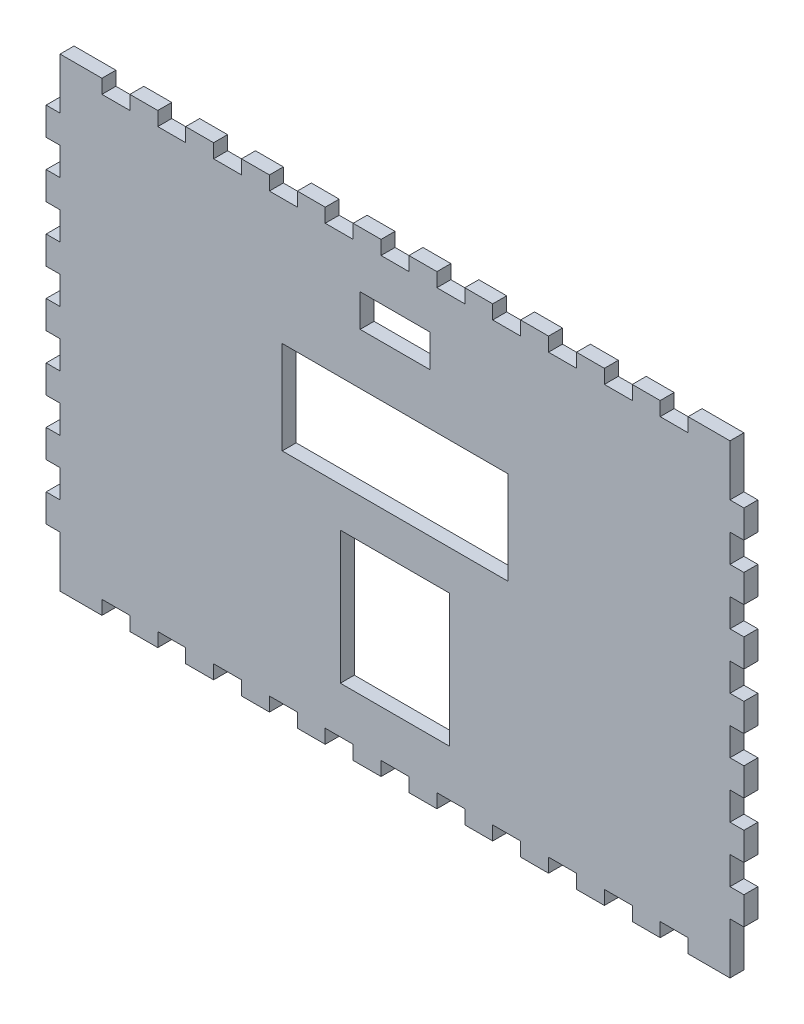
SolidWorks part; units mm, degrees
ref_plane "Front Plane" through (0, 0, 0) normal (0, 0, 1) x (1, 0, 0)
ref_plane "Top Plane" through (0, 0, 0) normal (0, 1, 0) x (1, 0, 0)
ref_plane "Right Plane" through (0, 0, 0) normal (1, 0, 0) x (0, 0, -1)
sketch "Model" plane through (0, 0, 0) normal (0, 0, 1) x (1, 0, 0)
  line L0 (209, 406) -> (209, 384)
  line L1 (209, 384) -> (203, 384)
  line L2 (203, 384) -> (203, 372)
  line L3 (203, 372) -> (209, 372)
  line L4 (209, 372) -> (209, 360)
  line L5 (209, 360) -> (203, 360)
  line L6 (203, 360) -> (203, 348)
  line L7 (203, 348) -> (209, 348)
  line L8 (209, 348) -> (209, 336)
  line L9 (209, 336) -> (203, 336)
  line L10 (203, 336) -> (203, 324)
  line L11 (203, 324) -> (209, 324)
  line L12 (209, 324) -> (209, 312)
  line L13 (209, 312) -> (203, 312)
  line L14 (203, 312) -> (203, 300)
  line L15 (203, 300) -> (209, 300)
  line L16 (209, 300) -> (209, 288)
  line L17 (209, 288) -> (203, 288)
  line L18 (203, 288) -> (203, 276)
  line L19 (203, 276) -> (209, 276)
  line L20 (209, 276) -> (209, 264)
  line L21 (209, 264) -> (203, 264)
  line L22 (203, 264) -> (203, 252)
  line L23 (203, 252) -> (209, 252)
  line L24 (209, 252) -> (209, 240)
  line L25 (209, 240) -> (203, 240)
  line L26 (203, 240) -> (203, 228)
  line L27 (203, 228) -> (209, 228)
  line L28 (209, 228) -> (209, 216)
  line L29 (209, 216) -> (209, 206)
  line L30 (209, 206) -> (227, 206)
  line L31 (227, 206) -> (227, 212)
  line L32 (227, 212) -> (239, 212)
  line L33 (239, 212) -> (239, 206)
  line L34 (239, 206) -> (251, 206)
  line L35 (251, 206) -> (251, 212)
  line L36 (251, 212) -> (263, 212)
  line L37 (263, 212) -> (263, 206)
  line L38 (263, 206) -> (275, 206)
  line L39 (275, 206) -> (275, 212)
  line L40 (275, 212) -> (287, 212)
  line L41 (287, 212) -> (287, 206)
  line L42 (287, 206) -> (299, 206)
  line L43 (299, 206) -> (299, 212)
  line L44 (299, 212) -> (311, 212)
  line L45 (311, 212) -> (311, 206)
  line L46 (311, 206) -> (323, 206)
  line L47 (323, 206) -> (323, 212)
  line L48 (323, 212) -> (335, 212)
  line L49 (335, 212) -> (335, 206)
  line L50 (335, 206) -> (347, 206)
  line L51 (347, 206) -> (347, 212)
  line L52 (347, 212) -> (359, 212)
  line L53 (359, 212) -> (359, 206)
  line L54 (359, 206) -> (371, 206)
  line L55 (371, 206) -> (371, 212)
  line L56 (371, 212) -> (383, 212)
  line L57 (383, 212) -> (383, 206)
  line L58 (383, 206) -> (395, 206)
  line L59 (395, 206) -> (395, 212)
  line L60 (395, 212) -> (407, 212)
  line L61 (407, 212) -> (407, 206)
  line L62 (407, 206) -> (419, 206)
  line L63 (419, 206) -> (419, 212)
  line L64 (419, 212) -> (431, 212)
  line L65 (431, 212) -> (431, 206)
  line L66 (431, 206) -> (443, 206)
  line L67 (443, 206) -> (443, 212)
  line L68 (443, 212) -> (455, 212)
  line L69 (455, 212) -> (455, 206)
  line L70 (455, 206) -> (467, 206)
  line L71 (467, 206) -> (467, 212)
  line L72 (467, 212) -> (479, 212)
  line L73 (479, 212) -> (479, 206)
  line L74 (479, 206) -> (491, 206)
  line L75 (491, 206) -> (497, 206)
  line L76 (497, 206) -> (497, 228)
  line L77 (497, 228) -> (503, 228)
  line L78 (503, 228) -> (503, 240)
  line L79 (503, 240) -> (497, 240)
  line L80 (497, 240) -> (497, 252)
  line L81 (497, 252) -> (503, 252)
  line L82 (503, 252) -> (503, 264)
  line L83 (503, 264) -> (497, 264)
  line L84 (497, 264) -> (497, 276)
  line L85 (497, 276) -> (503, 276)
  line L86 (503, 276) -> (503, 288)
  line L87 (503, 288) -> (497, 288)
  line L88 (497, 288) -> (497, 300)
  line L89 (497, 300) -> (503, 300)
  line L90 (503, 300) -> (503, 312)
  line L91 (503, 312) -> (497, 312)
  line L92 (497, 312) -> (497, 324)
  line L93 (497, 324) -> (503, 324)
  line L94 (503, 324) -> (503, 336)
  line L95 (503, 336) -> (497, 336)
  line L96 (497, 336) -> (497, 348)
  line L97 (497, 348) -> (503, 348)
  line L98 (503, 348) -> (503, 360)
  line L99 (503, 360) -> (497, 360)
  line L100 (497, 360) -> (497, 372)
  line L101 (497, 372) -> (503, 372)
  line L102 (503, 372) -> (503, 384)
  line L103 (503, 384) -> (497, 384)
  line L104 (497, 384) -> (497, 396)
  line L105 (497, 396) -> (497, 406)
  line L106 (497, 406) -> (479, 406)
  line L107 (479, 406) -> (479, 400)
  line L108 (479, 400) -> (467, 400)
  line L109 (467, 400) -> (467, 406)
  line L110 (467, 406) -> (455, 406)
  line L111 (455, 406) -> (455, 400)
  line L112 (455, 400) -> (443, 400)
  line L113 (443, 400) -> (443, 406)
  line L114 (443, 406) -> (431, 406)
  line L115 (431, 406) -> (431, 400)
  line L116 (431, 400) -> (419, 400)
  line L117 (419, 400) -> (419, 406)
  line L118 (419, 406) -> (407, 406)
  line L119 (407, 406) -> (407, 400)
  line L120 (407, 400) -> (395, 400)
  line L121 (395, 400) -> (395, 406)
  line L122 (395, 406) -> (383, 406)
  line L123 (383, 406) -> (383, 400)
  line L124 (383, 400) -> (371, 400)
  line L125 (371, 400) -> (371, 406)
  line L126 (371, 406) -> (359, 406)
  line L127 (359, 406) -> (359, 400)
  line L128 (359, 400) -> (347, 400)
  line L129 (347, 400) -> (347, 406)
  line L130 (347, 406) -> (335, 406)
  line L131 (335, 406) -> (335, 400)
  line L132 (335, 400) -> (323, 400)
  line L133 (323, 400) -> (323, 406)
  line L134 (323, 406) -> (311, 406)
  line L135 (311, 406) -> (311, 400)
  line L136 (311, 400) -> (299, 400)
  line L137 (299, 400) -> (299, 406)
  line L138 (299, 406) -> (287, 406)
  line L139 (287, 406) -> (287, 400)
  line L140 (287, 400) -> (275, 400)
  line L141 (275, 400) -> (275, 406)
  line L142 (275, 406) -> (263, 406)
  line L143 (263, 406) -> (263, 400)
  line L144 (263, 400) -> (251, 400)
  line L145 (251, 400) -> (251, 406)
  line L146 (251, 406) -> (239, 406)
  line L147 (239, 406) -> (239, 400)
  line L148 (239, 400) -> (227, 400)
  line L149 (227, 400) -> (227, 406)
  line L150 (227, 406) -> (215, 406)
  line L151 (215, 406) -> (209, 406)
extrude "Boss-Extrude1" add sketch "Model" along normal blind 6
sketch "Sketch2" plane through (0, 0, 6) normal (0, 0, 1) x (1, 0, 0)
  line L0 (368, 375) -> (503, 375)
  line L1 (338, 382) -> (368, 382)
  line L2 (338, 382) -> (338, 368)
  line L3 (338, 368) -> (368, 368)
  line L4 (368, 382) -> (368, 368)
  line L6 (338, 375) -> (203, 375)
  line L8 (401.5, 326) -> (497, 326)
  line L9 (304.5, 346) -> (401.5, 346)
  line L10 (304.5, 346) -> (304.5, 306)
  line L11 (304.5, 306) -> (401.5, 306)
  line L12 (401.5, 346) -> (401.5, 306)
  line L13 (497, 288) -> (497, 300) construction
  line L14 (304.5, 326) -> (209, 326)
  line L15 (209, 300) -> (209, 288) construction
  line L16 (503, 348) -> (503, 360) construction
  line L17 (203, 360) -> (203, 348) construction
  line L18 (371, 212) -> (383, 212) construction
  line L19 (329.5, 289) -> (376.5, 289)
  line L20 (329.5, 289) -> (329.5, 232)
  line L21 (329.5, 232) -> (376.5, 232)
  line L22 (376.5, 289) -> (376.5, 232)
  line L23 (376.5, 260.5) -> (497, 260.5)
  line L24 (497, 264) -> (497, 276) construction
  line L25 (329.5, 260.5) -> (209, 260.5)
  line L26 (209, 276) -> (209, 264) construction
  dimension "D1" = 30
  dimension "D2" = 14
  dimension "D3" = 97
  dimension "D4" = 40
  dimension "D5" = 22
  dimension "D6" = 17
  dimension "D7" = 20
  dimension "D8" = 57
  dimension "D9" = 47
extrude "Cut-Extrude1" cut sketch "Sketch2" against normal blind 6 contours L4 L1 L2 L3 | L12 L9 L10 L11 | L22 L19 L20 L21
